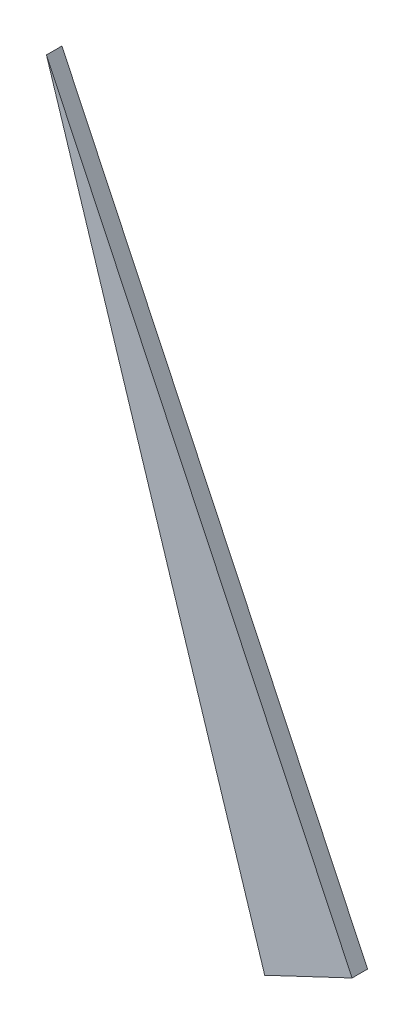
SolidWorks part; units mm, degrees
material "6061 Alloy"
ref_plane "Front Plane" through (0, 0, 0) normal (0, 0, 1) x (1, 0, 0)
ref_plane "Top Plane" through (0, 0, 0) normal (0, 1, 0) x (1, 0, 0)
ref_plane "Right Plane" through (0, 0, 0) normal (1, 0, 0) x (0, 0, -1)
sketch "Sketch1" plane through (0, 0, 0) normal (0, 0, 1) x (1, 0, 0)
  line L0 (38.9034, -80.2418) -> (67.6076, -66.6723)
  line L1 (67.6076, -66.6723) -> (-32.8065, 145.7388)
  line L2 (-32.8065, 145.7388) -> (38.9034, -80.2418)
  dimension "D1" = 31.75
  dimension "D3" = 234.95
extrude "Boss-Extrude1" add sketch "Sketch1" along normal blind 5.08
